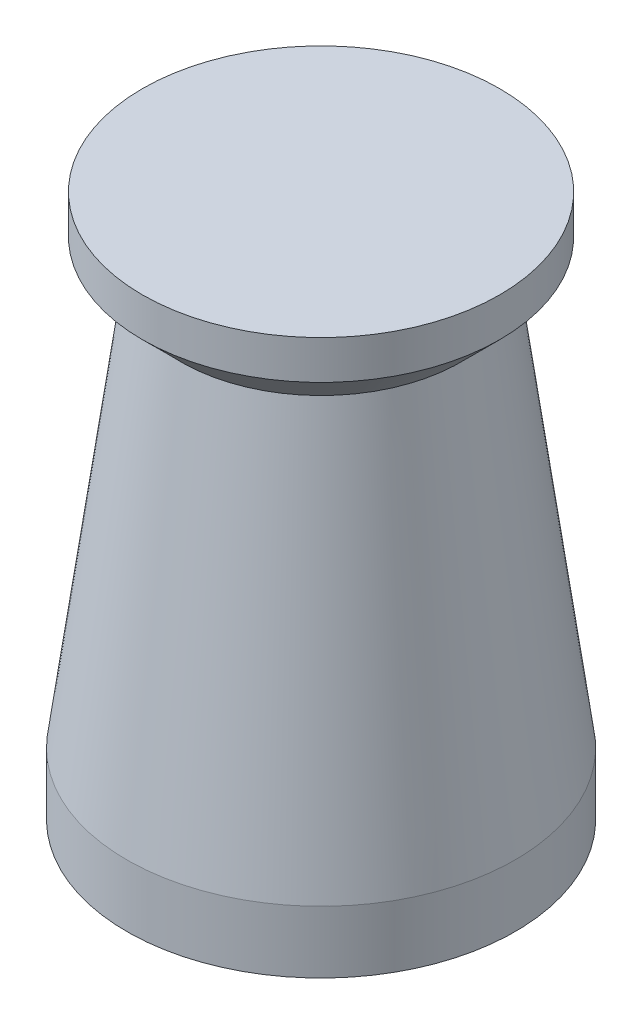
SolidWorks part; units mm, degrees
ref_plane "前视基准面" through (0, 0, 0) normal (0, 0, 1) x (1, 0, 0)
ref_plane "上视基准面" through (0, 0, 0) normal (0, 1, 0) x (1, 0, 0)
ref_plane "右视基准面" through (0, 0, 0) normal (1, 0, 0) x (0, 0, -1)
sketch "草图1" plane through (0, 0, 0) normal (0, 0, 1) x (1, 0, 0)
  line L0 (0, 0) -> (25, 0)
  line L1 (25, 0) -> (25, 8)
  line L4 (18, 60) -> (23, 65)
  line L5 (23, 70) -> (0, 70)
  line L6 (0, 70) -> (0, 0)
  line L7 (18, 60) -> (25, 8)
  line L8 (23, 70) -> (23, 65)
  point P4 (0, 0)
  point P7 (0, 0)
  point P10 (0, 0)
  point P12 (0, 0)
  point P13 (0, 0)
  point P14 (0, 0)
  point P15 (0, 0)
  point P16 (0, 0)
  point P17 (23, 63.0494)
  dimension "D1" = 25
  dimension "D2" = 8
  dimension "D3" = 23
  dimension "D4" = 18
  dimension "D5" = 10
  dimension "D6" = 5
  dimension "D7" = 70
revolve "旋转1" add sketch "草图1" angle 360 about L6
